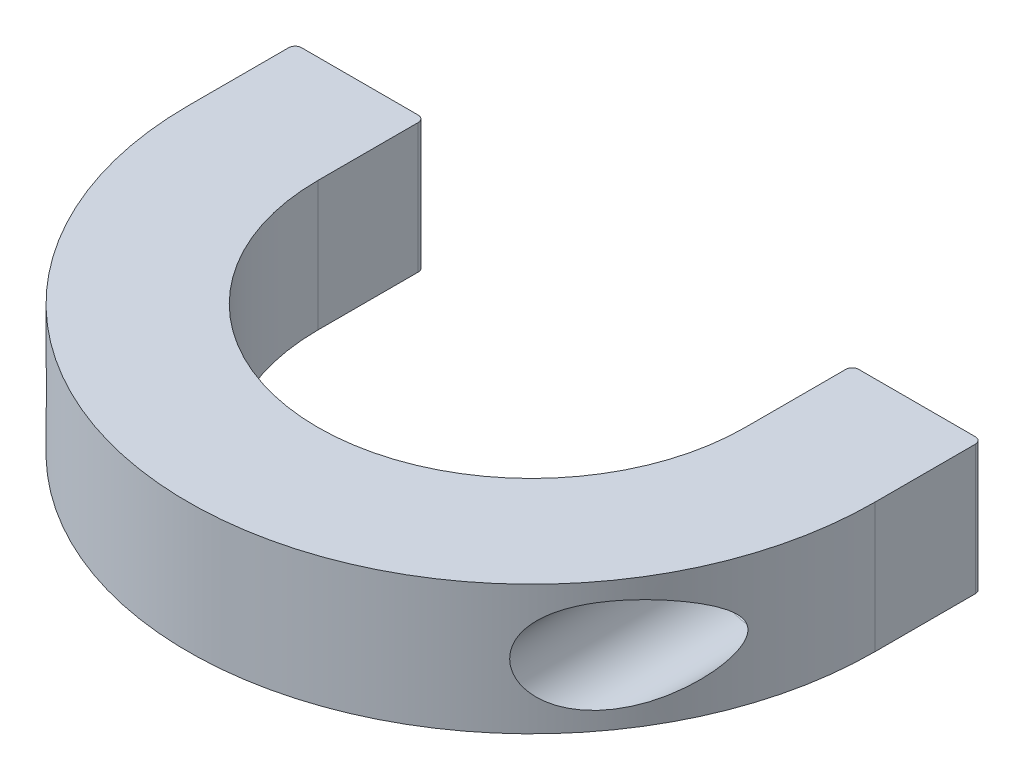
SolidWorks part; units mm, degrees
ref_plane "Front" through (0, 0, 0) normal (0, 0, 1) x (1, 0, 0)
ref_plane "Top" through (0, 0, 0) normal (0, 1, 0) x (1, 0, 0)
ref_plane "Right" through (0, 0, 0) normal (1, 0, 0) x (0, 0, -1)
sketch "Sketch1" plane through (0, 0, 0) normal (0, 1, 0) x (1, 0, 0)
  line L0 (-33, 0) -> (-33, 16.5)
  line L1 (33, 0) -> (33, 16.5)
  line L2 (-53, 0) -> (-53, 16.5)
  line L3 (53, 0) -> (53, 16.5)
  line L4 (-53, 16.5) -> (-33, 16.5)
  line L6 (33, 16.5) -> (53, 16.5)
  arc A0 (-33, 0) -> (33, 0) centre (0, 0) ccw
  arc A1 (-53, 0) -> (53, 0) centre (0, 0) ccw
  dimension "D1" = 66
  dimension "D2" = 16.5
  dimension "D3" = 20
extrude "Boss-Extrude1" add sketch "Sketch1" along normal blind 20
sketch "Sketch2" plane through (0, 0, -16.5) normal (0, 0, -1) x (-1, 0, 0)
  line L0 (-43, 20) -> (-43, 0) construction
  line L1 (-53, 20) -> (-33, 20) construction
  line L2 (-53, 0) -> (-33, 0) construction
  line L3 (-53, 10) -> (-33, 10) construction
  line L4 (-53, 20) -> (-53, 0) construction
  line L5 (-33, 20) -> (-33, 0) construction
  line L6 (0, 0) -> (0, 33.4814) construction
  circle A0 centre (-43, 10) radius 4.25
  circle A1 centre (43, 10) radius 4.25
  dimension "D1" = 8.5
extrude "Cut-Extrude1" cut sketch "Sketch2" against normal blind 60
sketch "Sketch3" plane through (0, 0, -16.5) normal (0, 0, -1) x (-1, 0, 0)
  circle A0 centre (-43, 10) radius 7.25
  circle A1 centre (43, 10) radius 7.25
  dimension "D1" = 14.5
extrude "Cut-Extrude2" cut sketch "Sketch3" against normal blind 50 from offset 25 offset against normal yes
fillet "Fillet1" radius 1 4 edges at (53, 10, -16.5) (33, 10, -16.5) (-33, 10, -16.5) (-53, 10, -16.5)
fillet "Fillet2" radius 0.5 6 edges at (-38.75, 10, -16.5) (38.75, 10, -16.5) (35.75, 10, 8.5) (38.75, 10, 8.5) (-47.25, 10, 8.5) (-50.25, 10, 8.5)
